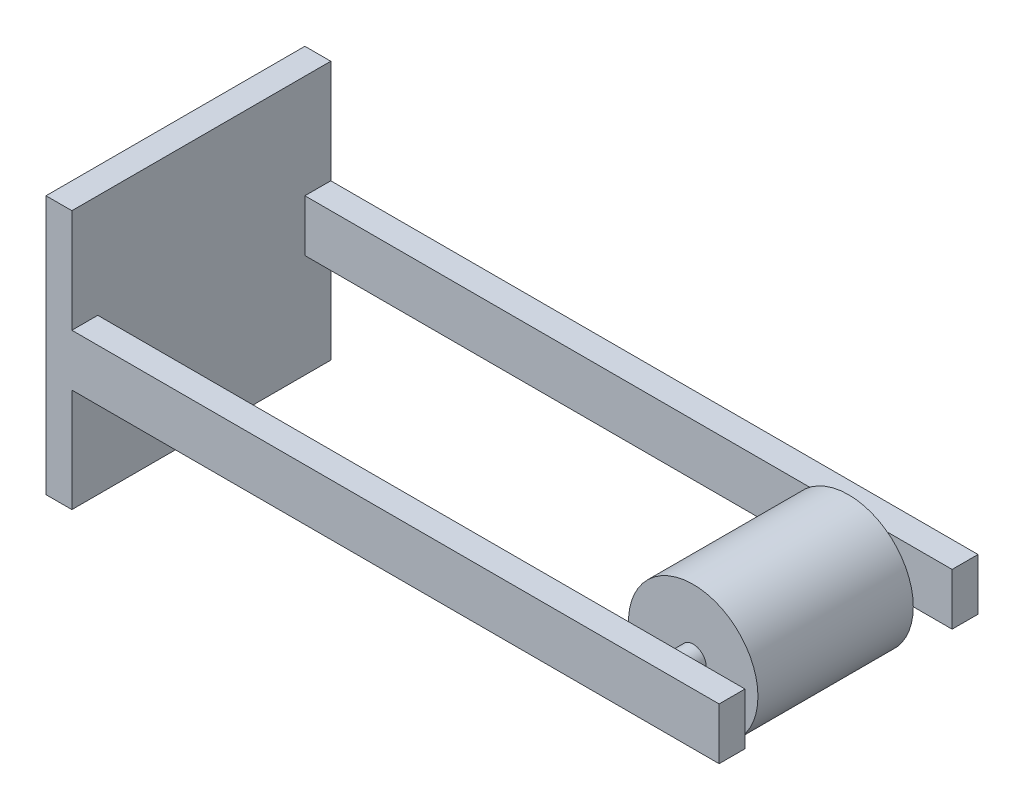
SolidWorks part; units mm, degrees
material "1.4000 (X6Cr13)"
ref_plane "前视基准面" through (0, 0, 0) normal (0, 0, 1) x (1, 0, 0)
ref_plane "上视基准面" through (0, 0, 0) normal (0, 1, 0) x (1, 0, 0)
ref_plane "右视基准面" through (0, 0, 0) normal (1, 0, 0) x (0, 0, -1)
sketch "草图1" plane through (0, 0, 0) normal (1, 0, 0) x (0, 0, -1)
  line L1 (0, 0) -> (10, 0)
  line L2 (0, 0) -> (0, 10)
  line L3 (0, 10) -> (10, 10)
  line L4 (10, 0) -> (10, 10)
extrude "凸台-拉伸1" add sketch "草图1" along normal blind 1
sketch "草图2" plane through (0, 0, 0) normal (0, 0, 1) x (1, 0, 0)
  line L0 (1, 10) -> (1, 0) construction
  line L6 (1, 6) -> (26, 6)
  line L7 (26, 6) -> (26, 4)
  line L8 (26, 4) -> (1, 4)
  line L9 (1, 4) -> (1, 6)
  point P0 (1, 5)
extrude "凸台-拉伸2" add sketch "草图2" against normal blind 1
sketch "草图3" plane through (0, 0, -10) normal (0, 0, -1) x (-1, 0, 0)
  line L0 (-1, 6) -> (-26, 6)
  line L1 (-26, 6) -> (-26, 4)
  line L2 (-26, 4) -> (-1, 4)
  line L3 (-1, 4) -> (-1, 6)
extrude "凸台-拉伸3" add sketch "草图3" against normal blind 1
sketch "草图4" plane through (0, 0, -1) normal (0, 0, -1) x (-1, 0, 0)
  circle A0 centre (-23, 5) radius 2.5
  point P2 (0, 0)
extrude "凸台-拉伸4" add sketch "草图4" along normal blind 8
sketch "草图5" plane through (0, 0, -1) normal (0, 0, 1) x (1, 0, 0)
  circle A0 centre (23, 5) radius 2.5
  circle A1 centre (23, 5) radius 0.5
  point P4 (0, 0)
extrude "切除-拉伸3" cut sketch "草图5" against normal blind 1 contours A0 | A1
sketch "草图6" plane through (0, 0, -9) normal (0, 0, -1) x (-1, 0, 0)
  circle A0 centre (-23, 5) radius 2.5
  circle A1 centre (-23, 5) radius 0.5
extrude "切除-拉伸4" cut sketch "草图6" against normal blind 1
